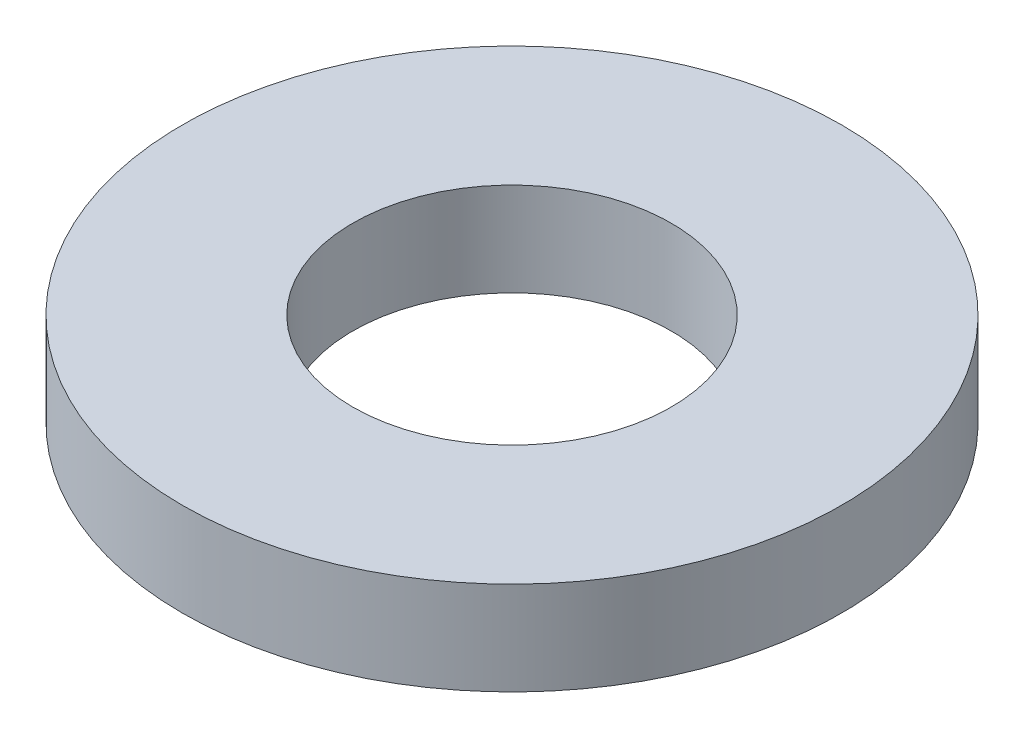
SolidWorks part; units mm, degrees
ref_plane "Alzado" through (0, 0, 0) normal (0, 0, 1) x (1, 0, 0)
ref_plane "Planta" through (0, 0, 0) normal (0, 1, 0) x (1, 0, 0)
ref_plane "Vista lateral" through (0, 0, 0) normal (1, 0, 0) x (0, 0, -1)
sketch "Croquis base" plane through (0, 0, 0) normal (0, 1, 0) x (1, 0, 0)
  circle A0 centre (0, 0) radius 3
  circle A1 centre (0, 0) radius 1.45
  dimension "D1" = 6
  dimension "D2" = 2.9
extrude "Saliente-Extruir1" add sketch "Croquis base" along normal blind 0.85
